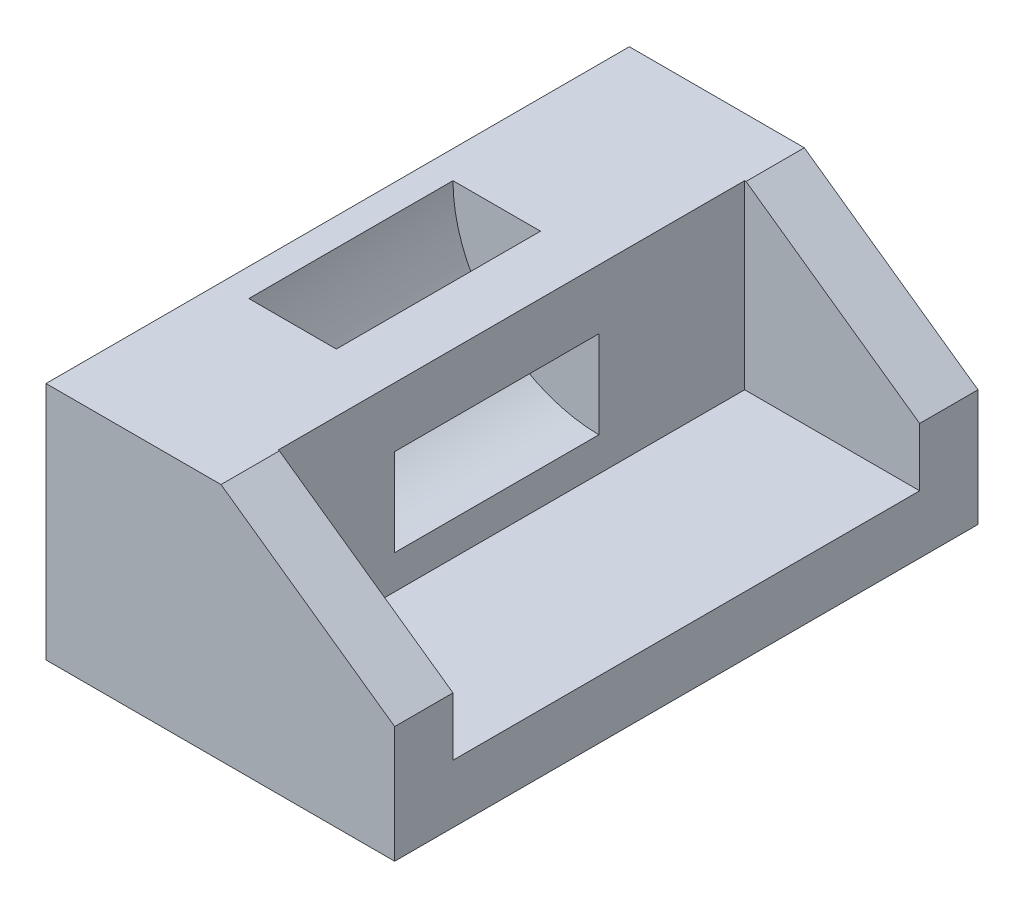
SolidWorks part; units mm, degrees
ref_plane "Front Plane" through (0, 0, 0) normal (0, 0, 1) x (1, 0, 0)
ref_plane "Top Plane" through (0, 0, 0) normal (0, 1, 0) x (1, 0, 0)
ref_plane "Right Plane" through (0, 0, 0) normal (1, 0, 0) x (0, 0, -1)
sketch "Sketch1" plane through (0, 0, 0) normal (0, 0, 1) x (1, 0, 0)
  line L0 (0, 0) -> (0, 20.5224)
  line L1 (0, 20.5224) -> (15, 20.5224)
  line L2 (0, 0) -> (29.8851, 0)
  line L3 (29.8851, 0) -> (29.8851, 10)
  line L4 (29.8851, 10) -> (15, 20.5224)
extrude "Boss-Extrude1" add sketch "Sketch1" along normal blind 50
sketch "Sketch4" plane through (29.8851, 0, 0) normal (1, 0, 0) x (0, 0, -1)
  line L0 (-50, 20.5224) -> (0, 20.5224) construction
  line L1 (-45, 20.5224) -> (-5, 20.5224)
  line L2 (-45, 20.5224) -> (-45, 5)
  line L3 (-45, 5) -> (-5, 5)
  line L4 (-5, 20.5224) -> (-5, 5)
  line L5 (-50, 0) -> (0, 0) construction
  line L6 (-50, 0) -> (-50, 10) construction
  dimension "D1" = 5
  dimension "D2" = 40
  dimension "D3" = 5
extrude "Cut-Extrude1" cut sketch "Sketch4" against normal blind 15
sketch "Sketch5" plane through (0, 20.5224, 0) normal (0, 1, 0) x (1, 0, 0)
  line L0 (15, 0) -> (0, 0) construction
  line L1 (2.3851, -35) -> (9.8851, -35)
  line L2 (2.3851, -35) -> (2.3851, -17.5)
  line L3 (2.3851, -17.5) -> (9.8851, -17.5)
  line L4 (9.8851, -35) -> (9.8851, -17.5)
  line L5 (14.8851, -45) -> (14.8851, -5) construction
  line L6 (15, -50) -> (15, 0) construction
  dimension "D1" = 17.5
  dimension "D2" = 17.5
  dimension "D3" = 7.5
  dimension "D4" = 5
revolve "Cut-Revolve1" cut sketch "Sketch5" angle 360 about L6
